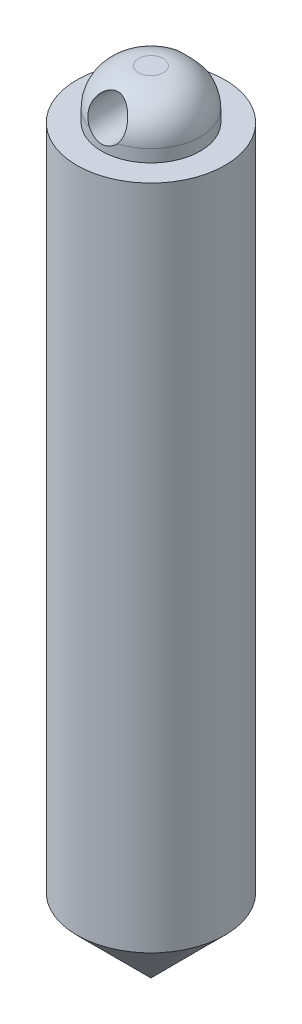
SolidWorks part; units mm, degrees
ref_plane "Front Plane" through (0, 0, 0) normal (0, 0, 1) x (1, 0, 0)
ref_plane "Top Plane" through (0, 0, 0) normal (0, 1, 0) x (1, 0, 0)
ref_plane "Right Plane" through (0, 0, 0) normal (1, 0, 0) x (0, 0, -1)
sketch "Sketch1" plane through (0, 0, 0) normal (0, 1, 0) x (1, 0, 0)
  circle A0 centre (0, 0) radius 30
  dimension "D1" = 60
extrude "Boss-Extrude1" add sketch "Sketch1" along normal blind 270
sketch "Sketch2" plane through (0, 270, 0) normal (0, 1, 0) x (1, 0, 0)
  circle A0 centre (0, 0) radius 29
  circle A1 centre (0, 0) radius 30 construction
  dimension "D1" = 1
extrude "Cut-Extrude1" cut sketch "Sketch2" against normal blind 270 from offset 2 offset against normal yes
sketch "Sketch3" plane through (0, 0, 0) normal (1, 0, 0) x (0, 0, -1)
  line L0 (0, 0) -> (0, -30)
  line L1 (0, -30) -> (30, 0)
  line L2 (30, 0) -> (0, 0)
  dimension "D1" = 30
revolve "Revolve1" add sketch "Sketch3" angle 360 about L0
sketch "Sketch5" plane through (0, 0, 0) normal (0, 0, 1) x (1, 0, 0)
  line L0 (30, 0) -> (-30, 0) construction
  line L1 (-28.6428, 35) -> (-18.6428, 35)
  line L2 (-28.6428, 35) -> (-28.6428, 50)
  line L3 (-28.6428, 50) -> (-18.6428, 50)
  line L4 (-18.6428, 35) -> (-18.6428, 50)
  line L5 (-28.6428, 35) -> (-18.6428, 50) construction
  line L6 (-28.6428, 50) -> (-18.6428, 35) construction
  line L7 (0, 35) -> (0, 58.2235) construction
  point P4 (-23.6428, 42.5)
  dimension "D1" = 10
  dimension "D2" = 15
  dimension "D3" = 35
  dimension "D4" = 18.6428
revolve "Revolve2" add sketch "Sketch5" angle 360 about L7
sketch "Sketch8" plane through (0, 270, 0) normal (0, 1, 0) x (1, 0, 0)
  circle A0 centre (0, 0) radius 20
  dimension "D1" = 40
extrude "Boss-Extrude2" add sketch "Sketch8" along normal blind 20
fillet "Fillet1" radius 15 1 edges at (0, 290, 20)
sketch "Sketch10" plane through (0, 0, 0) normal (0, 0, 1) x (1, 0, 0)
  circle A0 centre (0, 280) radius 7.5
  dimension "D1" = 15
extrude "Cut-Extrude2" cut sketch "Sketch10" against normal through all both and the other way through all
